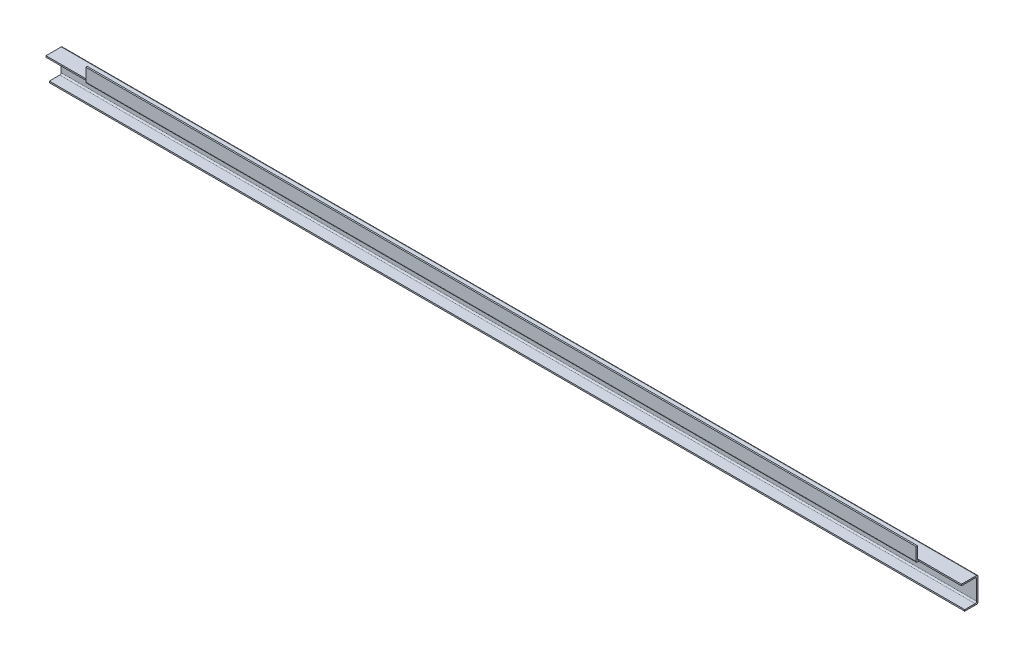
SolidWorks part; units mm, degrees
ref_plane "Front Plane" through (0, 0, 0) normal (0, 0, 1) x (1, 0, 0)
ref_plane "Top Plane" through (0, 0, 0) normal (0, 1, 0) x (1, 0, 0)
ref_plane "Right Plane" through (0, 0, 0) normal (1, 0, 0) x (0, 0, -1)
sketch "Sketch1" plane through (0, 0, 0) normal (1, 0, 0) x (0, 0, -1)
  line L0 (0, 0) -> (25, 0)
  line L1 (25, 0) -> (25, 47)
  line L2 (25, 47) -> (-13, 47)
  line L3 (-13, 47) -> (-13, 77)
  line L4 (0, -3) -> (28, -3)
  line L5 (28, -3) -> (28, 50)
  line L6 (28, 50) -> (-10, 50)
  line L7 (-10, 50) -> (-10, 77)
  line L8 (0, 0) -> (0, -3)
  line L9 (-13, 77) -> (-10, 77)
  dimension "D1" = 3
  dimension "D2" = 27
  dimension "D3" = 53
  dimension "D4" = 38
  dimension "D5" = 28
extrude "Boss-Extrude1" add sketch "Sketch1" along normal blind 1934
fillet "Fillet1" radius 3 6 edges at (967, -3, -28) (967, 50, -28) (967, 50, 10) (967, 0, -25) (967, 47, -25) (967, 47, 13)
sketch "Sketch2" plane through (0, 0, 13) normal (0, 0, 1) x (1, 0, 0)
  line L0 (0, 77) -> (90, 77)
  line L1 (1934, 77) -> (0, 77) construction
  line L2 (90, 77) -> (90, 47)
  line L3 (0, 47) -> (1934, 47) construction
  line L4 (90, 47) -> (0, 47)
  line L5 (0, 47) -> (0, 44) construction
  line L6 (0, 47) -> (0, 77)
  dimension "D1" = 90
extrude "Cut-Extrude1" cut sketch "Sketch2" against normal blind 6
sketch "Sketch3" plane through (0, 0, 13) normal (0, 0, 1) x (1, 0, 0)
  line L0 (1934, 77) -> (1844, 77)
  line L1 (1844, 77) -> (1844, 47)
  line L2 (0, 47) -> (1934, 47) construction
  line L3 (1844, 47) -> (1934, 47)
  line L4 (1934, 47) -> (1934, 77)
  dimension "D1" = 90
extrude "Cut-Extrude2" cut sketch "Sketch3" against normal blind 6
equation "\"side_door_bottom_R_3mm_length\"=1934.0"
equation "\"D1@Boss-Extrude1\"=\"side_door_bottom_L_3mm_length\""
equation "\"D1@Cut-Extrude1\"=\"side_door_bottom_R_3mm_Cut_RF_length\""
equation "\"D1@Sketch2\"=IIF ( ( \"DoorSeparator_LB_3mm_withHinge_exist\" ) = 1 , 90 , 30 )"
equation "\"D1@Sketch3\"=IIF ( ( \"DoorSeparator_LF_3mm_withHinge_exist\" ) = 1 , 90 , 30 )"
equation "\"CarBeamWidth\"=700.0"
equation "\"WheelWidth\"=650.0"
equation "\"Wheel_FrontBoxDistance\"=1390.0"
equation "\"MetalSheet_3mm_length\"=5030.0"
equation "\"MetalSheet_3mm_width\"=1923.0"
equation "\"MetalSheet_3mm_FloorCut_L_length\"=1764.0"
equation "\"MetalSheet_3mm_FloorCut_L_disdance\"=1665.0"
equation "\"MetalSheet_3mm_FloorCut_R_length\"=1764.0"
equation "\"MetalSheet_3mm_FloorCut_R_disdance\"=1665.0"
equation "\"indoorHeight\"=1940.0"
equation "\"haveDoor_R\"=1"
equation "\"1Bar_Side_RF_3mm_length\"=1493.0"
equation "\"1Bar_Side_RB_3mm_length\"=1493.0"
equation "\"DoorSeparator_RF_3mm_withHinge_toFrontDistance\"=1673.0"
equation "\"DoorSeparator_RF_3mm_withHinge_exist\"=1"
equation "\"DoorSeparator_RB_3mm_withHinge_toFrontDistance\"=3427.0"
equation "\"DoorSeparator_RB_3mm_withHinge_exist\"=1"
equation "\"Door_R1_L_open_Single_toFrontDistance\"=2547.5"
equation "\"Door_R1_L_open_Single_exist\"=1"
equation "\"Door_R1_R_open_Single_toFrontDistance\"=3422.0"
equation "\"Door_R1_R_open_Single_exist\"=1"
equation "\"x\"=66.0"
equation "\"da\"=62.0"
equation "\"SquareTube_length\"=1923.0"
equation "\"channelSteel_length\"=5030.0"
equation "\"SquareTube_inFront_AvgDistance\"=285.0"
equation "\"SquareTube_inFront_TotalCount\"=5"
equation "\"SquareTube_inFront1_cutDepth50_R\"=0.5"
equation "\"SquareTube_inFront1_cutDepth50_L\"=0.5"
equation "\"SquareTube_inFront2_cutDepth50_R\"=0.5"
equation "\"SquareTube_inFront2_cutDepth50_L\"=0.5"
equation "\"SquareTube_inFront3_cutDepth50_R\"=0.5"
equation "\"SquareTube_inFront3_cutDepth50_L\"=0.5"
equation "\"SquareTube_inFront4_cutDepth50_R\"=0.5"
equation "\"SquareTube_inFront4_cutDepth50_L\"=0.5"
equation "\"SquareTube_inFront5_cutDepth50_R\"=50"
equation "\"SquareTube_inFront5_cutDepth50_L\"=50"
equation "\"SquareTube_inFront6_cutDepth50_R\"=50"
equation "\"SquareTube_inFront6_cutDepth50_L\"=50"
equation "\"SquareTube_inFront7_cutDepth50_R\"=50"
equation "\"SquareTube_inFront7_cutDepth50_L\"=50"
equation "\"SquareTube_inFront8_cutDepth50_R\"=50"
equation "\"SquareTube_inFront8_cutDepth50_L\"=50"
equation "\"SquareTube_inFront9_cutDepth50_R\"=50"
equation "\"SquareTube_inFront9_cutDepth50_L\"=50"
equation "\"SquareTube_inFront10_cutDepth50_R\"=50"
equation "\"SquareTube_inFront10_cutDepth50_L\"=50"
equation "\"SquareTube_inFront11_cutDepth50_R\"=50"
equation "\"SquareTube_inFront11_cutDepth50_L\"=50"
equation "\"SquareTube_inFront12_cutDepth50_R\"=50"
equation "\"SquareTube_inFront12_cutDepth50_L\"=50"
equation "\"SquareTube_inFront13_cutDepth50_R\"=50"
equation "\"SquareTube_inFront13_cutDepth50_L\"=50"
equation "\"SquareTube_inFront14_cutDepth50_R\"=50"
equation "\"SquareTube_inFront14_cutDepth50_L\"=50"
equation "\"SquareTube_inBack_AvgDistance\"=333.125"
equation "\"SquareTube_inBack_TotalCount\"=9"
equation "\"SquareTube_inBack1_cutDepth50_R\"=50"
equation "\"SquareTube_inBack1_cutDepth50_L\"=50"
equation "\"SquareTube_inBack2_cutDepth50_R\"=50"
equation "\"SquareTube_inBack2_cutDepth50_L\"=50"
equation "\"SquareTube_inBack3_cutDepth50_R\"=50"
equation "\"SquareTube_inBack3_cutDepth50_L\"=50"
equation "\"SquareTube_inBack4_cutDepth50_R\"=50"
equation "\"SquareTube_inBack4_cutDepth50_L\"=50"
equation "\"SquareTube_inBack5_cutDepth50_R\"=50"
equation "\"SquareTube_inBack5_cutDepth50_L\"=50"
equation "\"SquareTube_inBack6_cutDepth50_R\"=0.5"
equation "\"SquareTube_inBack6_cutDepth50_L\"=0.5"
equation "\"SquareTube_inBack7_cutDepth50_R\"=0.5"
equation "\"SquareTube_inBack7_cutDepth50_L\"=0.5"
equation "\"SquareTube_inBack8_cutDepth50_R\"=0.5"
equation "\"SquareTube_inBack8_cutDepth50_L\"=0.5"
equation "\"boxLength\"=5100.0"
equation "\"boxWidth\"=1930.0"
equation "\"indoorHeight_para\"=25.0"
equation "\"rearLightHeight_para\"=265.0"
equation "\"doorColumnBar_A_FR_3mm_length_Cut\"=2310.0"
equation "\"A\"=0.0"
equation "\"side_door_bottom_R_3mm_toFrontDistance\"=1583.0"
equation "\"door_base_long7_R1_L_open_Single_height\"=1890.0"
equation "\"door_base_short7_R1_L_open_Single_height\"=1890.0"
equation "\"door_base_short7_R1_L_open_Single_width\"=864"
equation "\"door_base_long7_R1_R_open_Single_height\"=1890.0"
equation "\"door_base_short7_R1_R_open_Single_height\"=1890.0"
equation "\"door_base_short7_R1_R_open_Single_width\"=864"
equation "\"door_base_double_BL_height\"=1890.0"
equation "\"door_base_short7_BL_Single_height\"=1890.0"
equation "\"door_base_short7_BL_Single_width\"=864"
equation "\"door_base_long7_BR_Single_height\"=1890.0"
equation "\"door_base_short7_BR_Single_height\"=1890.0"
equation "\"door_base_short7_BR_Single_width\"=864"
equation "\"doorColumnBar_A_FL_3mm_length_Cut\"=2310.0"
equation "\"B\"=0.0"
equation "\"haveDoor_L\"=1"
equation "\"side_door_bottom_L_3mm_length\"=1934.0"
equation "\"side_door_bottom_L_3mm_toFrontDistance\"=1583.0"
equation "\"1Bar_Side_LF_3mm_length\"=1493.0"
equation "\"1Bar_Side_LB_3mm_length\"=1493.0"
equation "\"DoorSeparator_LF_3mm_withHinge_toFrontDistance\"=1673.0"
equation "\"DoorSeparator_LF_3mm_withHinge_exist\"=1"
equation "\"DoorSeparator_LB_3mm_withHinge_toFrontDistance\"=3427.0"
equation "\"DoorSeparator_LB_3mm_withHinge_exist\"=1"
equation "\"Door_L1_L_open_Single_toFrontDistance\"=3422.0"
equation "\"Door_L1_L_open_Single_exist\"=1"
equation "\"door_base_long7_L1_L_open_Single_height\"=1890.0"
equation "\"door_base_short7_L1_L_open_Single_height\"=1890.0"
equation "\"door_base_short7_L1_L_open_Single_width\"=864"
equation "\"Door_L1_R_open_Single_toFrontDistance\"=2547.5"
equation "\"Door_L1_R_open_Single_exist\"=1"
equation "\"door_base_long7_L1_R_open_Single_height\"=1890.0"
equation "\"door_base_short7_L1_R_open_Single_height\"=1890.0"
equation "\"door_base_short7_L1_R_open_Single_width\"=864"
